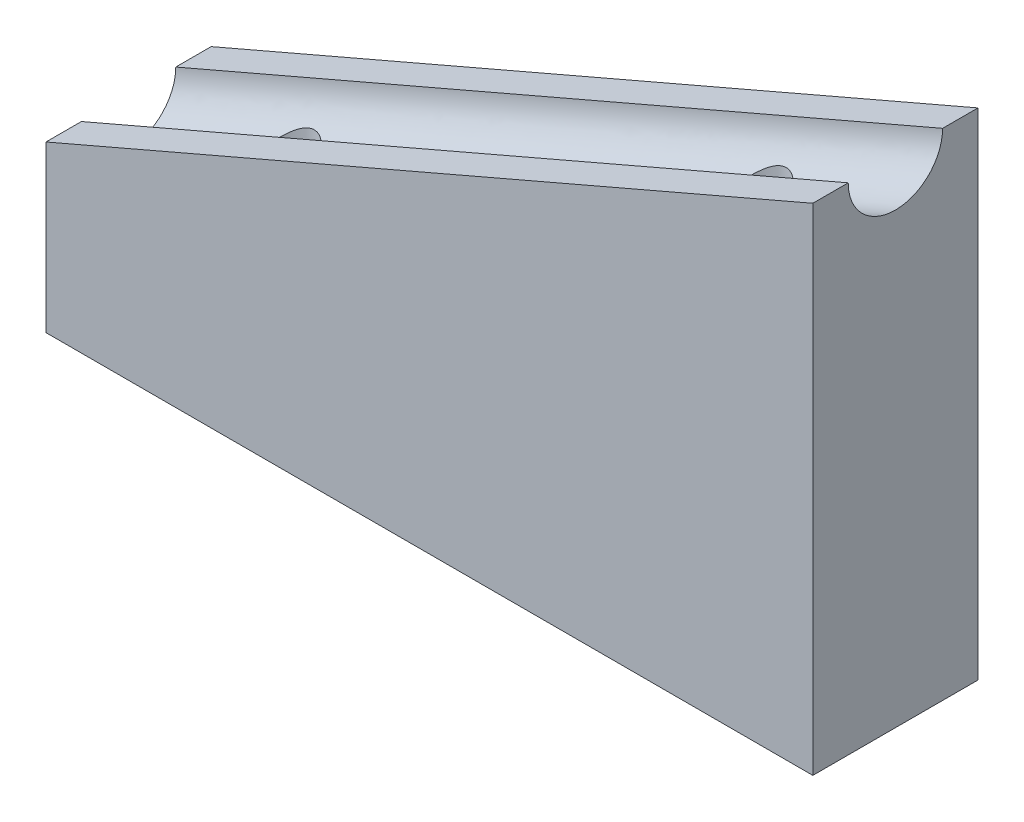
SolidWorks part; units mm, degrees
ref_plane "前视基准面" through (0, 0, 0) normal (0, 0, 1) x (1, 0, 0)
ref_plane "上视基准面" through (0, 0, 0) normal (0, 1, 0) x (1, 0, 0)
ref_plane "右视基准面" through (0, 0, 0) normal (1, 0, 0) x (0, 0, -1)
sketch "草图1" plane through (0, 0, 0) normal (0, 1, 0) x (1, 0, 0)
  line L1 (-16.25, -3.5) -> (16.25, -3.5)
  line L2 (-16.25, -3.5) -> (-16.25, 3.5)
  line L3 (-16.25, 3.5) -> (16.25, 3.5)
  line L4 (16.25, -3.5) -> (16.25, 3.5)
  line L5 (-16.25, -3.5) -> (16.25, 3.5) construction
  line L6 (-16.25, 3.5) -> (16.25, -3.5) construction
  point P0 (0, 0)
  dimension "D1" = 32.5
  dimension "D2" = 7
extrude "凸台-拉伸1" add sketch "草图1" along normal blind 21
sketch "草图2" plane through (0, 0, 0) normal (0, -1, 0) x (1, 0, 0)
  line L0 (-10, 0) -> (10, 0) construction
  circle A0 centre (-10, 0) radius 1.35
  circle A1 centre (10, 0) radius 1.35
  point P4 (0, 0)
  dimension "D2" = 2.7
  dimension "D1" = 20
extrude "切除-拉伸1" cut sketch "草图2" against normal up to next
sketch "草图3" plane through (0, 0, 3.5) normal (0, 0, 1) x (1, 0, 0)
  line L0 (-16.25, 21) -> (-16.25, 7)
  line L1 (-16.25, 21) -> (-16.25, 0) construction
  line L2 (-16.25, 7) -> (16.25, 21)
  line L3 (16.25, 21) -> (-16.25, 21)
  dimension "D1" = 14
extrude "切除-拉伸2" cut sketch "草图3" against normal up to next
sketch "草图4" plane through (-16.25, 0, 0) normal (-1, 0, 0) x (0, 0, 1)
  line L0 (-3.5, 7) -> (3.5, 7) construction
  line L1 (-2, 7) -> (2, 7)
  arc A0 (-2, 7) -> (2, 7) centre (0, 7) ccw
  dimension "D1" = 2
sketch "草图5" plane through (-5.0868, 11.8087, 0) normal (-0.3956, 0.9184, 0) x (0.9184, 0.3956, 0)
  line L0 (-12.1548, 0) -> (23.2323, 0)
  line L1 (-12.1548, 3.5) -> (-12.1548, -3.5) construction
  line L2 (23.2323, -3.5) -> (23.2323, 3.5) construction
sweep "切除-扫描1" cut profiles "草图4" path "草图5"
